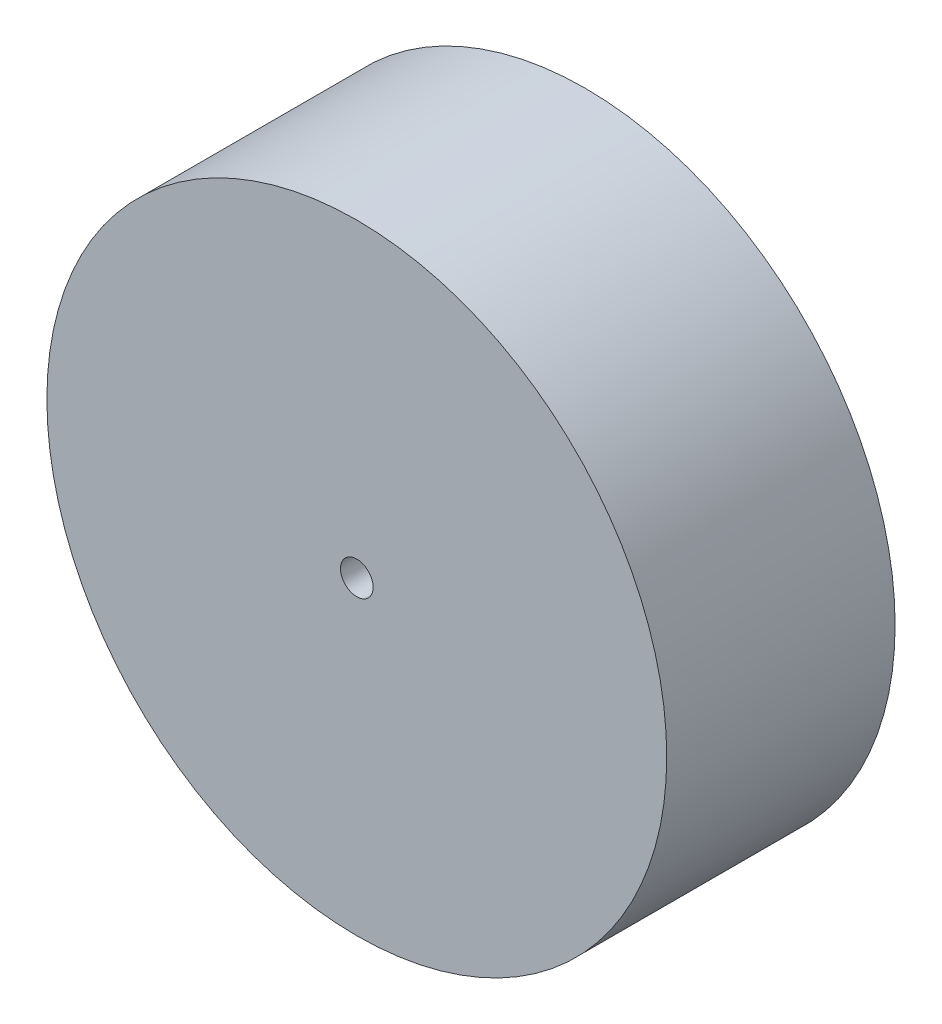
SolidWorks part; units mm, degrees
ref_plane "正面" through (0, 0, 0) normal (0, 0, 1) x (1, 0, 0)
ref_plane "平面" through (0, 0, 0) normal (0, 1, 0) x (1, 0, 0)
ref_plane "右側面" through (0, 0, 0) normal (1, 0, 0) x (0, 0, -1)
sketch "ｽｹｯﾁ2" plane through (0, 0, 0) normal (0, 0, 1) x (1, 0, 0)
  circle A0 centre (0, 0) radius 19
  dimension "D1" = 38
extrude "ﾎﾞｽ - 押し出し1" add sketch "ｽｹｯﾁ2" along normal blind 14
sketch "ｽｹｯﾁ3" plane through (0, 0, 0) normal (0, 0, 1) x (1, 0, 0)
  circle A0 centre (0, 0) radius 1
  dimension "D1" = 2
extrude "ｶｯﾄ - 押し出し3" cut sketch "ｽｹｯﾁ3" along normal through all and the other way through all
